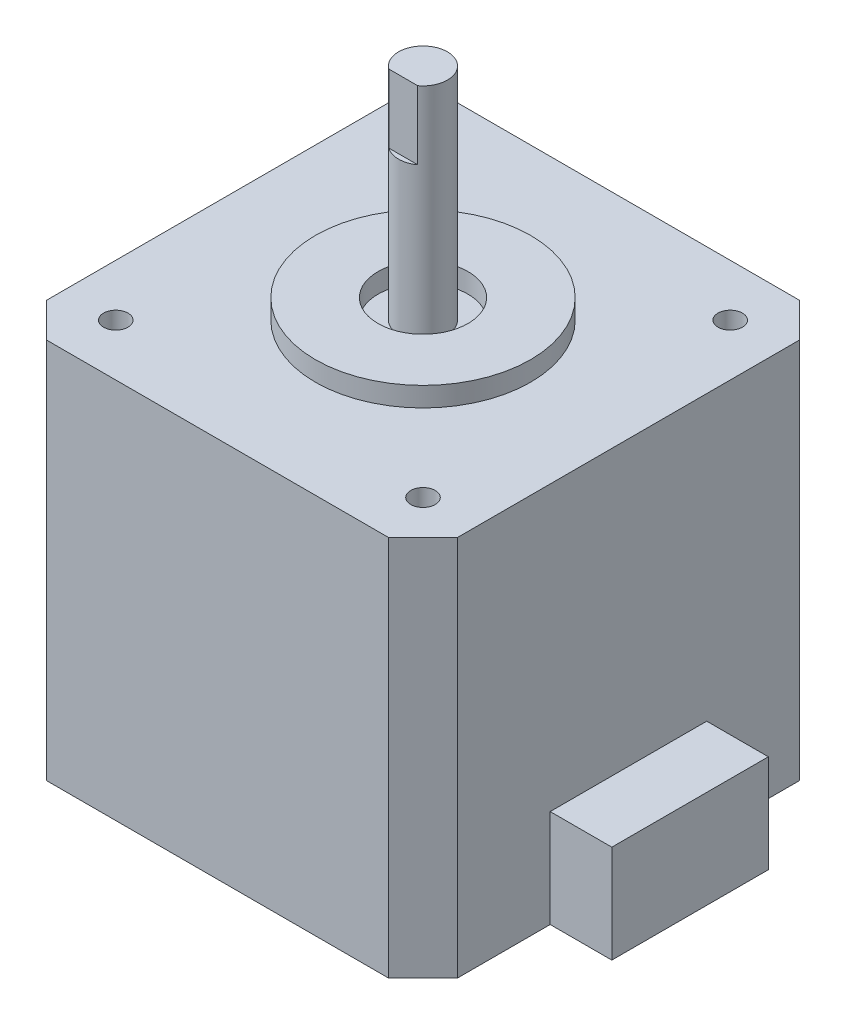
SolidWorks part; units mm, degrees
ref_plane "Plan de face" through (0, 0, 0) normal (0, 0, 1) x (1, 0, 0)
ref_plane "Plan de dessus" through (0, 0, 0) normal (0, 1, 0) x (1, 0, 0)
ref_plane "Plan de droite" through (0, 0, 0) normal (1, 0, 0) x (0, 0, -1)
sketch "Esquisse1" plane through (0, 0, 0) normal (0, 1, 0) x (1, 0, 0)
  line L0 (3.5355, 2.5496) -> (0, 6.0851)
  line L1 (0, 6.0851) -> (0, 41.014)
  line L2 (0, 41.014) -> (3.5355, 44.5496)
  line L3 (3.5355, 44.5496) -> (38.4645, 44.5496)
  line L4 (38.4645, 44.5496) -> (42, 41.014)
  line L5 (42, 41.014) -> (42, 6.0851)
  line L6 (42, 6.0851) -> (38.4645, 2.5496)
  line L7 (38.4645, 2.5496) -> (3.5355, 2.5496)
  dimension "D1" = 42
  dimension "D2" = 42
  dimension "D3" = 5
  dimension "D4" = 5
  dimension "D5" = 5
  dimension "D6" = 5
  dimension "D7" = 135
extrude "Boss.-Extru.1" add sketch "Esquisse1" along normal blind 39
sketch "Esquisse2" plane through (0, 39, 0) normal (0, 1, 0) x (1, 0, 0)
  line L1 (38.4645, 44.5496) -> (3.5355, 44.5496) construction
  line L2 (0, 41.014) -> (0, 6.0851) construction
  line L4 (42, 6.0851) -> (42, 41.014) construction
  line L5 (3.5355, 2.5496) -> (38.4645, 2.5496) construction
  circle A0 centre (5.3, 39.2496) radius 1.25
  circle A1 centre (36.7, 39.2496) radius 1.25
  circle A2 centre (36.7, 7.8496) radius 1.25
  circle A3 centre (5.3, 7.8496) radius 1.25
  dimension "D1" = 2.5
  dimension "D4" = 2.5
  dimension "D6" = 2.5
  dimension "D8" = 2.5
  dimension "D2" = 5.3
  dimension "D3" = 5.3
  dimension "D5" = 5.3
  dimension "D7" = 5.3
extrude "Enlèv. mat.-Extru.1" cut sketch "Esquisse2" against normal blind 39
sketch "Esquisse3" plane through (0, 39, 0) normal (0, 1, 0) x (1, 0, 0)
  line L0 (5.3, 7.8496) -> (36.7, 39.2496) construction
  line L1 (36.7, 7.8496) -> (5.3, 39.2496) construction
  circle A0 centre (21, 23.5496) radius 11
  circle A1 centre (21, 23.5496) radius 4.6
  dimension "D1" = 22
  dimension "D2" = 9.2
extrude "Boss.-Extru.2" add sketch "Esquisse3" along normal blind 2
sketch "Esquisse4" plane through (0, 39, 0) normal (0, 1, 0) x (1, 0, 0)
  circle A0 centre (21, 23.5496) radius 2.5
  dimension "D1" = 5
extrude "Boss.-Extru.3" add sketch "Esquisse4" along normal blind 22.5
ref_point "Point1"
ref_point "Point2"
ref_plane "Plan1" through (21, 0, 0) normal (1, 0, 0) x (0, 0, -1)
sketch "Esquisse8" plane through (0, 61.5, 0) normal (0, 1, 0) x (1, 0, 0)
  line L0 (22.4749, 21.531) -> (19.5251, 21.531)
  circle A0 centre (21, 23.5496) radius 2.5 construction
  arc A1 (22.4749, 21.531) -> (19.5251, 21.531) centre (21, 23.5496) cw
extrude "Enlèv. mat.-Extru.4" cut sketch "Esquisse8" against normal blind 7 contours L0 A1
sketch "Esquisse9" plane through (42, 0, 0) normal (1, 0, 0) x (0, 0, -1)
  line L0 (6.0851, 0) -> (41.014, 0) construction
  line L1 (15.549, 0) -> (31.549, 0)
  line L2 (15.549, 0) -> (15.549, 10)
  line L3 (15.549, 10) -> (31.549, 10)
  line L4 (31.549, 0) -> (31.549, 10)
  line L6 (41.014, 39) -> (41.014, 0) construction
  dimension "D1" = 16
  dimension "D2" = 10
  dimension "D3" = 9.465
extrude "Boss.-Extru.4" add sketch "Esquisse9" along normal blind 6.3
